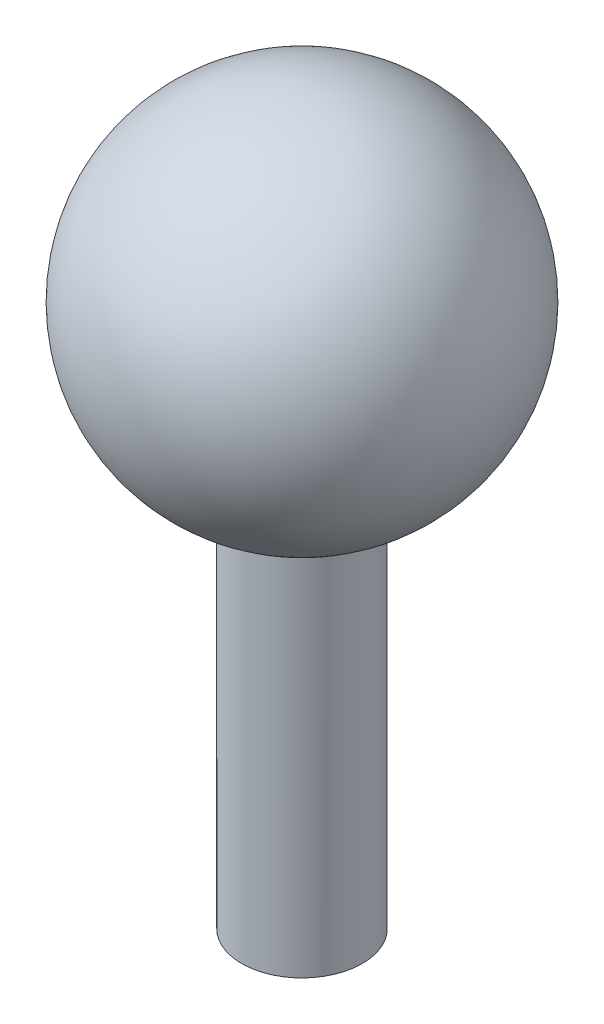
SolidWorks part; units mm, degrees
ref_plane "Front Plane" through (0, 0, 0) normal (0, 0, 1) x (1, 0, 0)
ref_plane "Top Plane" through (0, 0, 0) normal (0, 1, 0) x (1, 0, 0)
ref_plane "Right Plane" through (0, 0, 0) normal (1, 0, 0) x (0, 0, -1)
sketch "Sketch1" plane through (0, 0, 0) normal (0, 0, 1) x (1, 0, 0)
  line L0 (0, 0) -> (-5, 0)
  line L1 (-5, 0) -> (-5, 30.8579)
  line L16 (0, 0) -> (0, 60)
  arc A0 (0, 60) -> (-5, 30.8579) centre (0, 45) ccw
  dimension "D1" = 30
  dimension "D2" = 60
  dimension "D3" = 5
revolve "Revolve1" add sketch "Sketch1" angle 360 about L16
sketch "Sketch2" plane through (0, 0, 0) normal (0, -1, 0) x (-1, 0, 0)
  circle A0 centre (0, 0) radius 5
  circle A1 centre (0, -22) radius 5
  circle A2 centre (0, 22) radius 5
  dimension "D1" = 10
  dimension "D3" = 10
  dimension "D4" = 10
  dimension "D2" = 22
  dimension "D5" = 22
sketch "Sketch3" plane through (0, 100, 0) normal (0, 1, 0) x (1, 0, 0)
  circle A0 centre (0, 0) radius 31
  circle A1 centre (0, 0) radius 31 construction
